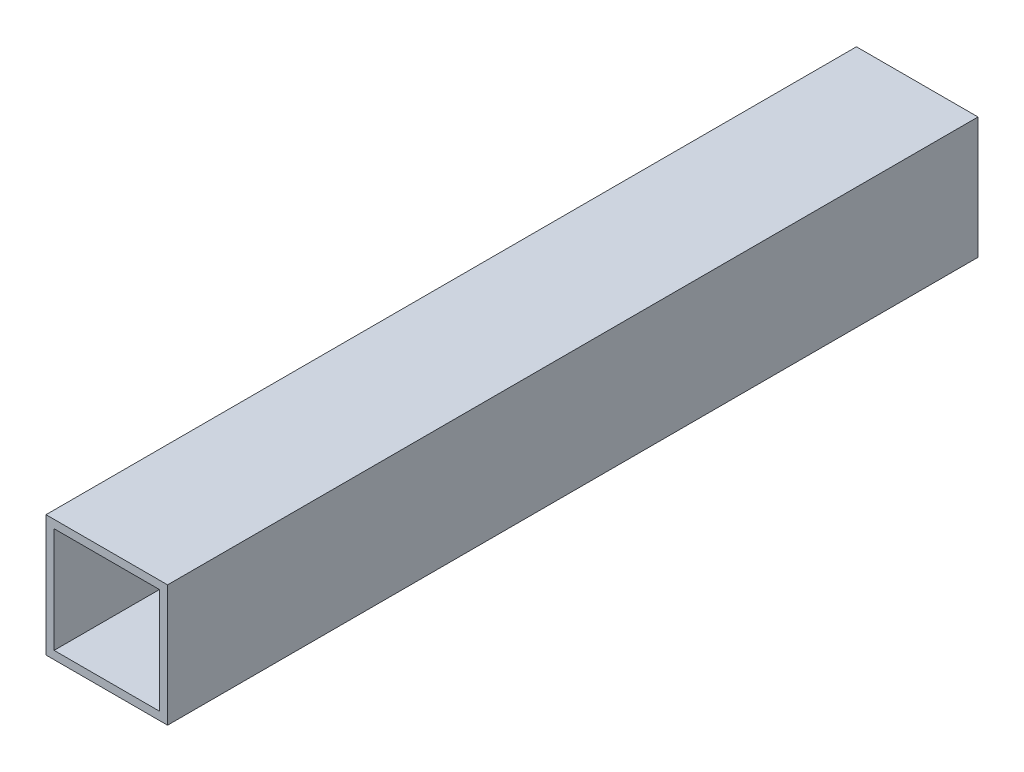
SolidWorks part; units mm, degrees
ref_plane "前视基准面" through (0, 0, 0) normal (0, 0, 1) x (1, 0, 0)
ref_plane "上视基准面" through (0, 0, 0) normal (0, 1, 0) x (1, 0, 0)
ref_plane "右视基准面" through (0, 0, 0) normal (1, 0, 0) x (0, 0, -1)
other "Configuration Table"
sketch "草图1" plane through (0, 0, 0) normal (0, 0, 1) x (1, 0, 0)
  line L1 (0, 0) -> (15, 0)
  line L2 (0, 0) -> (0, -15)
  line L3 (0, -15) -> (15, -15)
  line L4 (15, 0) -> (15, -15)
  point P4 (0, 0)
  dimension "D1" = 15
  dimension "D2" = 15
extrude "拉伸-薄壁1" add sketch "草图1" along normal blind 100 thin
